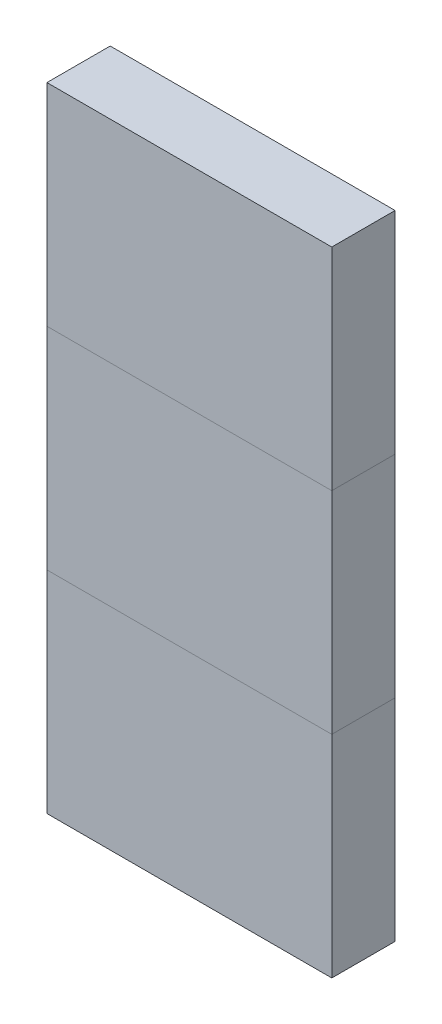
SolidWorks part; units mm, degrees
other "top block"
other "middle block"
other "bottom block"
material "ABS"
ref_plane "Front" through (0, 0, 0) normal (0, 0, 1) x (1, 0, 0)
ref_plane "Top" through (0, 0, 0) normal (0, 1, 0) x (1, 0, 0)
ref_plane "Right" through (0, 0, 0) normal (1, 0, 0) x (0, 0, -1)
sketch "Sketch1" plane through (0, 0, 0) normal (0, 0, 1) x (1, 0, 0)
  line L1 (-28.575, 63.5) -> (28.575, 63.5)
  line L2 (-28.575, 63.5) -> (-28.575, -63.5)
  line L3 (-28.575, -63.5) -> (28.575, -63.5)
  line L4 (28.575, 63.5) -> (28.575, -63.5)
  line L5 (-28.575, 63.5) -> (28.575, -63.5) construction
  line L6 (-28.575, -63.5) -> (28.575, 63.5) construction
  point P0 (0, 0)
  dimension "D1" = 57.15
  dimension "D2" = 127
extrude "Boss-Extrude1" add sketch "Sketch1" along normal mid plane 12.7
sketch "Sketch2" plane through (0, 0, 0) normal (0, 1, 0) x (1, 0, 0)
  line L1 (-25.4, 1.5875) -> (25.4, 1.5875)
  line L2 (-25.4, 1.5875) -> (-25.4, -1.5875)
  line L3 (-25.4, -1.5875) -> (25.4, -1.5875)
  line L4 (25.4, 1.5875) -> (25.4, -1.5875)
  line L5 (-25.4, 1.5875) -> (25.4, -1.5875) construction
  line L6 (-25.4, -1.5875) -> (25.4, 1.5875) construction
  line L7 (-19, 4.7625) -> (19, 4.7625)
  line L8 (-19, 4.7625) -> (-19, -4.7625)
  line L9 (-19, -4.7625) -> (19, -4.7625)
  line L10 (19, 4.7625) -> (19, -4.7625)
  line L11 (-19, 4.7625) -> (19, -4.7625) construction
  line L12 (-19, -4.7625) -> (19, 4.7625) construction
  point P0 (0, 0)
  point P5 (0, 0)
  dimension "D1" = 50.8
  dimension "D2" = 3.175
  dimension "D3" = 9.525
  dimension "D4" = 38
extrude "Cut-Extrude1" cut sketch "Sketch2" against normal mid plane 114.3 contours L8 L1 L2 L3 | L10 L1 L8 L3 | L10 L7 L8 L1 | L10 L3 L8 L9 | L1 L10 L3 L4
sketch "Sketch3" plane through (0, 0, 6.35) normal (0, 0, 1) x (1, 0, 0)
  line L0 (-28.575, 21.1667) -> (28.575, 21.1667)
  line L1 (-28.575, 63.5) -> (-28.575, -63.5) construction
  line L2 (28.575, -63.5) -> (28.575, 63.5) construction
  line L3 (28.575, 21.1667) -> (28.575, 63.5) construction
  line L4 (28.575, 21.1667) -> (28.575, -21.1667) construction
  line L5 (28.575, -21.1667) -> (28.575, -63.5) construction
  line L6 (28.575, -21.1667) -> (-28.575, -21.1667)
split "Split1" trim tools "Sketch3" bodies to split 102 resulting bodies 103 104 105
sketch "Sketch4" plane through (0, 57.15, 0) normal (0, -1, 0) x (1, 0, 0)
  line L1 (-19, 4.7625) -> (19, 4.7625)
  line L2 (-19, 4.7625) -> (-19, 1.5875)
  line L3 (-19, 1.5875) -> (19, 1.5875)
  line L4 (19, 4.7625) -> (19, 1.5875)
  line L5 (19, -1.5875) -> (-19, -1.5875)
  line L6 (19, -1.5875) -> (19, -4.7625)
  line L7 (19, -4.7625) -> (-19, -4.7625)
  line L8 (-19, -1.5875) -> (-19, -4.7625)
extrude "Boss-Extrude2" add sketch "Sketch4" along normal blind 6.6
other "Save Bodies1"
other "Save Bodies2"
